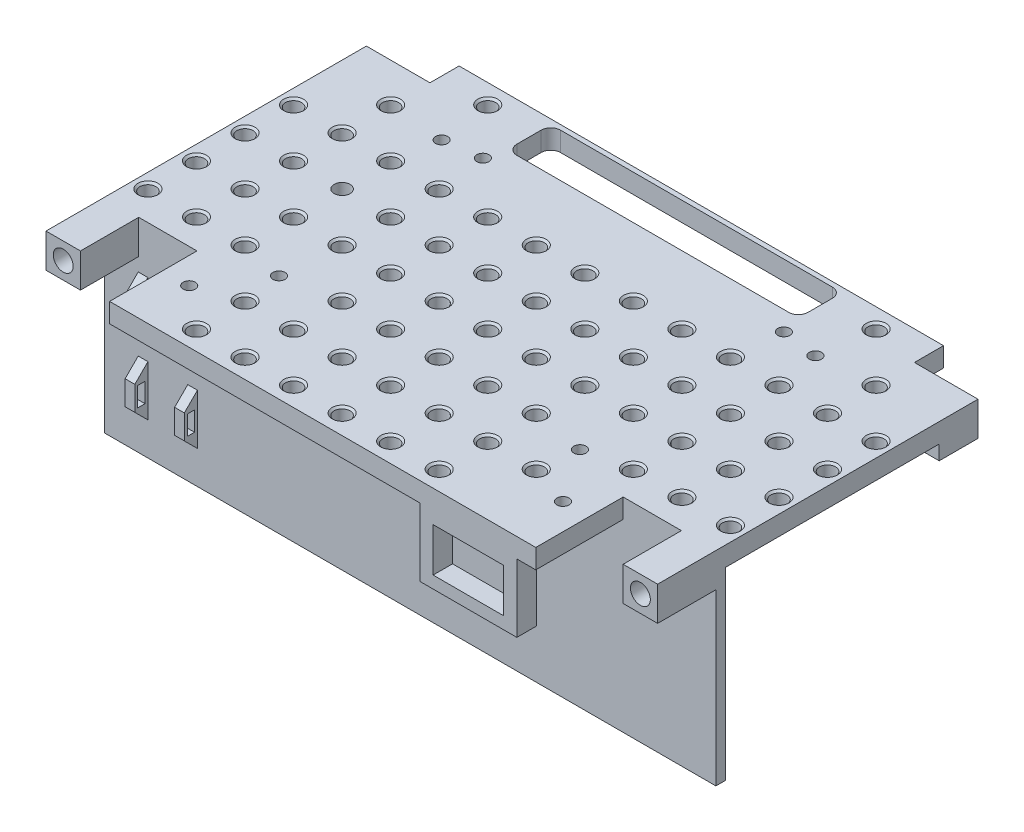
SolidWorks part; units mm, degrees
ref_plane "Front Plane" through (0, 0, 0) normal (0, 0, 1) x (1, 0, 0)
ref_plane "Top Plane" through (0, 0, 0) normal (0, 1, 0) x (1, 0, 0)
ref_plane "Right Plane" through (0, 0, 0) normal (1, 0, 0) x (0, 0, -1)
sketch "Sketch1" plane through (0, 0, 0) normal (0, 1, 0) x (1, 0, 0)
  line L0 (-63, 0) -> (63, 0) construction
  line L1 (-63, -33) -> (-55.9, -33)
  line L2 (-63, -33) -> (-63, 33)
  line L3 (-63, 33) -> (-55.9, 33)
  line L4 (63, -33) -> (63, 33)
  line L5 (-63, -33) -> (63, 33) construction
  line L6 (-63, 33) -> (63, -33) construction
  line L8 (-55.9, 33) -> (-55.9, 40)
  line L9 (-55.9, 40) -> (55.9, 40)
  line L10 (55.9, 33) -> (55.9, 40)
  line L11 (55.9, 33) -> (63, 33)
  line L12 (55.9, -33) -> (55.9, -40)
  line L13 (-55.9, -40) -> (55.9, -40)
  line L14 (-55.9, -33) -> (-55.9, -40)
  line L15 (55.9, -33) -> (63, -33)
  point P0 (0, 0)
  point P10 (0, 40)
  dimension "D1" = 126
  dimension "D2" = 66
  dimension "D3" = 7.1
  dimension "D4" = 7
extrude "Boss-Extrude1" add sketch "Sketch1" along normal blind 4
sketch "Sketch3" plane through (0, 0, 0) normal (0, -1, 0) x (1, 0, 0)
  line L0 (-63, -33) -> (-63, 33) construction
  line L1 (-55.9, -33) -> (-63, -33)
  line L2 (-55.9, -33) -> (-55.9, -25)
  line L3 (-55.9, -25) -> (-63, -25)
  line L4 (-63, -33) -> (-63, -25)
  dimension "D1" = 8
extrude "Boss-Extrude3" add sketch "Sketch3" along normal blind 3
sketch "Sketch4" plane through (0, 0, -33) normal (0, 0, -1) x (-1, 0, 0)
  line L0 (63, -3) -> (55.9, 4) construction
  circle A0 centre (59.45, 0.5) radius 2.05
  dimension "D1" = 4.1
extrude "Cut-Extrude1" cut sketch "Sketch4" against normal blind 7
mirror "Mirror1" about plane through (0, 0, 0) normal (1, 0, 0) of "Cut-Extrude1", "Boss-Extrude3"
mirror "Mirror2" about plane through (0, 0, 0) normal (0, 0, 1) of "Cut-Extrude1", "Boss-Extrude3", "Mirror1"
sketch "Sketch5" plane through (0, 4, 0) normal (0, 1, 0) x (1, 0, 0)
  line L0 (55.9, 40) -> (-55.9, 40) construction
  line L1 (-30, 38) -> (30, 38)
  line L2 (-30, 38) -> (-30, 29)
  line L3 (-30, 29) -> (30, 29)
  line L4 (30, 38) -> (30, 29)
  point P4 (0, 29)
  dimension "D1" = 2
  dimension "D2" = 9
  dimension "D3" = 60
extrude "Cut-Extrude2" cut sketch "Sketch5" against normal through all
sketch "Sketch6" plane through (0, 4, 0) normal (0, 1, 0) x (1, 0, 0)
  line L1 (-38.5, -28) -> (38.5, -28) construction
  line L2 (-38.5, -28) -> (-38.5, 24) construction
  line L3 (-38.5, 24) -> (38.5, 24) construction
  line L4 (38.5, -28) -> (38.5, 24) construction
  line L5 (-38.5, -28) -> (38.5, 24) construction
  line L6 (-38.5, 24) -> (38.5, -28) construction
  circle A0 centre (-38.5, 24) radius 1.25
  circle A1 centre (38.5, 24) radius 1.25
  circle A2 centre (38.5, -28) radius 1.25
  circle A3 centre (-38.5, -28) radius 1.25
  point P0 (0, -2)
  point P9 (0, -2)
  dimension "D4" = 2.5
  dimension "D1" = 77
  dimension "D2" = 52
  dimension "D3" = 2
fillet "Fillet1" radius 2 4 edges at (-30, 2, -38) (-30, 2, -29) (30, 2, -38) (30, 2, -29)
sketch "Sketch7" plane through (0, 4, 0) normal (0, 1, 0) x (1, 0, 0)
  line L0 (55.9, 33) -> (55.9, 40) construction
  line L1 (-55.9, 40) -> (55.9, 40)
  line L2 (-55.9, 40) -> (-55.9, 39)
  line L3 (-55.9, 39) -> (55.9, 39)
  line L4 (55.9, 40) -> (55.9, 39)
  line L5 (-55.9, -33) -> (-55.9, -40) construction
  line L6 (55.9, -40) -> (-55.9, -40)
  line L7 (55.9, -40) -> (55.9, -39)
  line L8 (55.9, -39) -> (-55.9, -39)
  line L9 (-55.9, -40) -> (-55.9, -39)
  dimension "D1" = 1
  dimension "D2" = 1
extrude "Cut-Extrude3" cut sketch "Sketch7" against normal through all
sketch "Sketch8" plane through (0, 0, 0) normal (0, -1, 0) x (1, 0, 0)
  line L0 (63, 25) -> (63, -25) construction
  line L1 (63, 21) -> (-63, 21)
  line L2 (63, 21) -> (63, 19)
  line L3 (63, 19) -> (-63, 19)
  line L4 (-63, 21) -> (-63, 19)
  line L5 (-63, -25) -> (-63, 25) construction
  line L7 (55.9, 39) -> (-55.9, 39) construction
  dimension "D1" = 20
  dimension "D2" = 2
extrude "Boss-Extrude4" add sketch "Sketch8" along normal blind 38
sketch "Sketch9" plane through (0, 4, 0) normal (0, 1, 0) x (1, 0, 0)
  line L0 (63, -21) -> (-63, -21) construction
  line L1 (-55.9, -39) -> (-43.9, -39)
  line L2 (-55.9, -39) -> (-55.9, -21)
  line L3 (-55.9, -21) -> (-43.9, -21)
  line L4 (-43.9, -39) -> (-43.9, -21)
  dimension "D1" = 12
extrude "Cut-Extrude4" cut sketch "Sketch9" against normal blind 10
sketch "Sketch10" plane through (0, -3, 0) normal (0, -1, 0) x (1, 0, 0)
  line L1 (-63, 25) -> (-55.9, 25)
  line L2 (-63, 25) -> (-63, 21)
  line L3 (-63, 21) -> (-55.9, 21)
  line L4 (-55.9, 25) -> (-55.9, 21)
  line L5 (55.9, 25) -> (63, 25)
  line L6 (55.9, 25) -> (55.9, 21)
  line L7 (55.9, 21) -> (63, 21)
  line L8 (63, 25) -> (63, 21)
extrude "Boss-Extrude5" add sketch "Sketch10" against normal up to surface (3 mm away) up to face at (29.4143, 0, 29)
ref_plane "Plane2" through (-56, 0, 0) normal (-1, 0, 0) x (0, 0, 1)
sketch "Sketch12" plane through (-56, 0, 0) normal (-1, 0, 0) x (0, 0, 1)
  line L0 (21, -5.8) -> (21, -16.2)
  line L1 (21, -38) -> (21, -3) construction
  line L2 (21, -16.2) -> (23.7, -13.5)
  line L3 (23.7, -13.5) -> (23.7, -8.5)
  line L4 (23.7, -8.5) -> (21, -5.8)
  line L5 (23.7, -11) -> (21, -11) construction
  line L6 (21, -3) -> (33, -3) construction
  line L7 (23.1, -9) -> (21.6, -9)
  line L8 (23.1, -9) -> (23.1, -13)
  line L9 (23.1, -13) -> (21.6, -13)
  line L10 (21.6, -9) -> (21.6, -13)
  line L11 (21, -20.8) -> (21, -31.2)
  line L12 (21, -31.2) -> (23.7, -28.5)
  line L13 (23.7, -28.5) -> (23.7, -23.5)
  line L14 (23.7, -23.5) -> (21, -20.8)
  line L15 (23.1, -24) -> (21.6, -24)
  line L16 (23.1, -24) -> (23.1, -28)
  line L17 (23.1, -28) -> (21.6, -28)
  line L18 (21.6, -24) -> (21.6, -28)
  line L19 (23.7, -26) -> (21, -26) construction
  point P13 (22.35, -11)
  point P14 (23.1, -11)
  dimension "D1" = 1.5
  dimension "D2" = 0.6
  dimension "D3" = 0.6
  dimension "D4" = 4
  dimension "D5" = 45
  dimension "D6" = 5
  dimension "D7" = 8
  dimension "D8" = 2
extrude "Boss-Extrude6" add sketch "Sketch12" against normal blind 2
ref_plane "Plane3" through (-49.9, 0, 0) normal (1, 0, 0) x (0, 0, -1)
mirror "Mirror3" about plane through (-49.9, 0, 0) normal (1, 0, 0) of "Boss-Extrude6"
sketch "Sketch13" plane through (0, 0, 0) normal (0, -1, 0) x (1, 0, 0)
  line L0 (-28, -29) -> (28, -29) construction
  line L1 (-20, -20.5) -> (20, -20.5)
  line L2 (-20, -20.5) -> (-20, -22.5)
  line L3 (-20, -22.5) -> (20, -22.5)
  line L4 (20, -20.5) -> (20, -22.5)
  point P4 (0, -22.5)
  dimension "D1" = 40
  dimension "D2" = 2
  dimension "D3" = 6.5
extrude "Boss-Extrude7" add sketch "Sketch13" along normal up to surface (38 mm away) up to face at (0, -38, 20)
sketch "Sketch14" plane through (0, 0, 0) normal (1, 0, 0) x (0, 0, -1)
  line L0 (-19, -19) -> (20.5, -19) construction
  line L1 (-19, -38) -> (-19, 0) construction
  line L2 (20.5, -38) -> (20.5, 0) construction
  line L3 (0.75, -38) -> (0.75, 0) construction
  line L4 (-19, 0) -> (25, 0) construction
  line L5 (-21, -31.2) -> (-23.7, -28.5) construction
  line L6 (-23.1, -24) -> (-21.6, -24) construction
  line L7 (-23.1, -28) -> (-23.1, -24) construction
  line L8 (-21.6, -28) -> (-23.1, -28) construction
  line L9 (-21.6, -24) -> (-21.6, -28) construction
  line L10 (-21, -20.8) -> (-21, -31.2) construction
  line L11 (-23.7, -23.5) -> (-21, -20.8) construction
  line L12 (-23.7, -28.5) -> (-23.7, -23.5) construction
  line L13 (-23.1, -13) -> (-23.1, -9) construction
  line L14 (-23.1, -9) -> (-21.6, -9) construction
  line L15 (-21.6, -9) -> (-21.6, -13) construction
  line L16 (-21.6, -13) -> (-23.1, -13) construction
  line L17 (-21, -5.8) -> (-21, -16.2) construction
  line L18 (-21, -16.2) -> (-23.7, -13.5) construction
  line L19 (-23.7, -13.5) -> (-23.7, -8.5) construction
  line L20 (-23.7, -8.5) -> (-21, -5.8) construction
  line L21 (-21, -31.2) -> (-23.7, -28.5) construction
  line L22 (-23.1, -24) -> (-21.6, -24) construction
  line L23 (-23.1, -28) -> (-23.1, -24) construction
  line L24 (-21.6, -28) -> (-23.1, -28) construction
  line L25 (-21.6, -24) -> (-21.6, -28) construction
  line L26 (-21, -20.8) -> (-21, -31.2) construction
  line L27 (-23.7, -23.5) -> (-21, -20.8) construction
  line L28 (-23.7, -28.5) -> (-23.7, -23.5) construction
  line L29 (-23.1, -13) -> (-23.1, -9) construction
  line L30 (-23.1, -9) -> (-21.6, -9) construction
  line L31 (-21.6, -9) -> (-21.6, -13) construction
  line L32 (-21.6, -13) -> (-23.1, -13) construction
  line L33 (-21, -5.8) -> (-21, -16.2) construction
  line L34 (-21, -16.2) -> (-23.7, -13.5) construction
  line L35 (-23.7, -13.5) -> (-23.7, -8.5) construction
  line L36 (-23.7, -8.5) -> (-21, -5.8) construction
  line L37 (25.2, -8.5) -> (22.5, -5.8)
  line L38 (25.2, -13.5) -> (25.2, -8.5)
  line L39 (22.5, -16.2) -> (25.2, -13.5)
  line L40 (22.5, -5.8) -> (22.5, -16.2)
  line L41 (23.1, -13) -> (24.6, -13)
  line L42 (23.1, -9) -> (23.1, -13)
  line L43 (24.6, -9) -> (23.1, -9)
  line L44 (24.6, -13) -> (24.6, -9)
  line L45 (25.2, -28.5) -> (25.2, -23.5)
  line L46 (25.2, -23.5) -> (22.5, -20.8)
  line L47 (22.5, -20.8) -> (22.5, -31.2)
  line L48 (23.1, -24) -> (23.1, -28)
  line L49 (23.1, -28) -> (24.6, -28)
  line L50 (24.6, -28) -> (24.6, -24)
  line L51 (24.6, -24) -> (23.1, -24)
  line L52 (22.5, -31.2) -> (25.2, -28.5)
  point P11 (0.75, -19)
extrude "Boss-Extrude8" add sketch "Sketch14" along normal mid plane 2
sketch "Sketch15" plane through (0, 0, 0) normal (1, 0, 0) x (0, 0, -1)
  line L0 (20.5, 0) -> (20.5, -5)
  line L1 (20.5, -38) -> (20.5, 0) construction
  line L2 (20.5, -5) -> (17.6132, 0)
  line L3 (-19, 0) -> (25, 0) construction
  line L4 (17.6132, 0) -> (20.5, 0)
  dimension "D1" = 60
  dimension "D2" = 5
extrude "Boss-Extrude9" add sketch "Sketch15" against normal up to surface and the other way up to surface up to face at (-20, -19, -21.5) other way up to face at (20, -19, -21.5)
sketch "Sketch16" plane through (0, 0, 39) normal (0, 0, 1) x (1, 0, 0)
  line L0 (40, 0) -> (20, -14) construction
  line L1 (40, 0) -> (20, 0)
  line L2 (40, 0) -> (40, -14)
  line L3 (40, -14) -> (20, -14)
  line L4 (20, 0) -> (20, -14)
  line L5 (55.9, 0) -> (-43.9, 0) construction
  line L6 (22.75, -2.5) -> (37.25, -2.5)
  line L7 (22.75, -2.5) -> (22.75, -11.5)
  line L8 (22.75, -11.5) -> (37.25, -11.5)
  line L9 (37.25, -2.5) -> (37.25, -11.5)
  line L10 (22.75, -2.5) -> (37.25, -11.5) construction
  line L11 (22.75, -11.5) -> (37.25, -2.5) construction
  line L12 (63, -38) -> (63, -3) construction
  point P5 (30, -7)
  dimension "D1" = 20
  dimension "D2" = 14
  dimension "D3" = 14.5
  dimension "D4" = 9
  dimension "D5" = 23
extrude "Boss-Extrude10" add sketch "Sketch16" against normal blind 4
sketch "Sketch17" plane through (0, 0, 0) normal (0, -1, 0) x (1, 0, 0)
  line L6 (-43.9, 21) -> (-55.9, 21) construction
  line L7 (55.9, 39) -> (43.9, 39)
  line L8 (55.9, 39) -> (55.9, 21)
  line L9 (55.9, 21) -> (43.9, 21)
  line L10 (43.9, 39) -> (43.9, 21)
  line L13 (-43.9, 39) -> (-43.9, 21) construction
extrude "Cut-Extrude5" cut sketch "Sketch17" against normal through all
sketch "Sketch18" plane through (0, 4, 0) normal (0, 1, 0) x (1, 0, 0)
  line L5 (-55.9, 39) -> (55.9, 39) construction
  line L6 (55.9, 33) -> (49.9, 33)
  line L7 (55.9, 33) -> (55.9, 39)
  line L8 (55.9, 39) -> (49.9, 39)
  line L9 (49.9, 33) -> (49.9, 39)
  line L11 (-55.9, 33) -> (-49.9, 33)
  line L12 (-55.9, 33) -> (-55.9, 39)
  line L13 (-55.9, 39) -> (-49.9, 39)
  line L14 (-49.9, 33) -> (-49.9, 39)
extrude "Cut-Extrude6" cut sketch "Sketch18" against normal through all
sketch "Sketch20" plane through (0, 4, 0) normal (0, 1, 0) x (1, 0, 0)
  line L0 (-31, 25) -> (31, -17) construction
  line L1 (-31, 25) -> (31, 25) construction
  line L2 (-31, 25) -> (-31, -17) construction
  line L3 (-31, -17) -> (31, -17) construction
  line L4 (31, 25) -> (31, -17) construction
  line L5 (-38.5, 26) -> (38.5, 26) construction
  line L6 (-38.5, 26) -> (-38.5, -26) construction
  line L7 (-38.5, -26) -> (38.5, -26) construction
  line L8 (38.5, 26) -> (38.5, -26) construction
  line L11 (38.5, 26) -> (-38.5, -26) construction
  circle A0 centre (-31, 25) radius 3 construction
  circle A1 centre (-31, -17) radius 3 construction
  circle A2 centre (31, -17) radius 3 construction
  circle A3 centre (31, 25) radius 3 construction
  circle A4 centre (-38.5, 26) radius 3 construction
  circle A5 centre (38.5, 26) radius 3 construction
  circle A6 centre (38.5, -26) radius 3 construction
  circle A7 centre (-38.5, -26) radius 3 construction
  point P18 (0, 4)
  dimension "D3" = 6
  dimension "D1" = 42
  dimension "D2" = 62
  dimension "D4" = 4
  dimension "D6" = 77
  dimension "D7" = 52
sketch "Sketch22" plane through (0, 4, 0) normal (0, 1, 0) x (1, 0, 0)
  circle A0 centre (-31, 25) radius 1.25
  circle A1 centre (31, 25) radius 1.25
  circle A2 centre (31, -17) radius 1.25
  circle A3 centre (-31, -17) radius 1.25
  dimension "D1" = 2.5
extrude "Cut-Extrude7" cut sketch "Sketch22" against normal up to surface (4 mm away) up to face at (15, 0, 33.5)
sketch "Sketch23" plane through (0, 4, 0) normal (0, 1, 0) x (1, 0, 0)
  line L0 (-63, 0) -> (63, 0) construction
  line L1 (63, -33) -> (63, 33) construction
  line L2 (0, -39) -> (0, 39) construction
  line L3 (-49.9, 39) -> (49.9, 39) construction
  line L4 (-63, -5) -> (63, -5) construction
  line L5 (-63, -15) -> (63, -15) construction
  line L9 (-10, -5) -> (-10, -15) construction
  line L10 (-20, -5) -> (-20, -15) construction
  line L11 (-30, -5) -> (-30, -15) construction
  line L12 (-40, -5) -> (-40, -15) construction
  line L13 (-50, -5) -> (-50, -15) construction
  line L14 (-60, -5) -> (-60, -15) construction
  circle A0 centre (0, -5) radius 1.65
  circle A1 centre (0, -15) radius 1.65
  circle A2 centre (-10, -5) radius 1.65
  circle A3 centre (-20, -5) radius 1.65
  circle A4 centre (-30, -5) radius 1.65
  circle A5 centre (-40, -5) radius 1.65
  circle A6 centre (-50, -5) radius 1.65
  circle A7 centre (-60, -5) radius 1.65
  circle A8 centre (-60, -15) radius 1.65
  circle A9 centre (-50, -15) radius 1.65
  circle A10 centre (-40, -15) radius 1.65
  circle A11 centre (-20, -15) radius 1.65
  circle A12 centre (-10, -15) radius 1.65
  point P6 (0, 0)
  point P11 (0, 0)
  point P18 (0, -5)
  point P21 (0, -15)
  dimension "D1" = 3.3
  dimension "D4" = 10
  dimension "D2" = 5
  dimension "D3" = 10
  dimension "D5" = 10
  dimension "D6" = 10
  dimension "D7" = 10
  dimension "D8" = 10
  dimension "D9" = 10
extrude "Cut-Extrude8" cut sketch "Sketch23" against normal through all
mirror "Mirror4" about plane through (0, 0, 0) normal (0, 0, 1) of "Cut-Extrude8"
mirror "Mirror5" about plane through (0, 0, 0) normal (1, 0, 0) of "Mirror4", "Cut-Extrude8"
sketch "Sketch24" plane through (0, 4, 0) normal (0, 1, 0) x (1, 0, 0)
  line L0 (-40, 15) -> (-20, 15) construction
  line L1 (20, 15) -> (40, 15) construction
  line L2 (-40, 15) -> (-40, 39) construction
  line L3 (-49.9, 39) -> (49.9, 39) construction
  line L4 (-50, 15) -> (-50, 33) construction
  line L5 (-49.9, 33) -> (-63, 33) construction
  line L6 (-50, 25) -> (-40, 25) construction
  line L7 (-50, 35) -> (-40, 35) construction
  line L8 (40, 15) -> (40, 39) construction
  line L9 (50, 15) -> (50, 33) construction
  line L10 (63, 33) -> (49.9, 33) construction
  line L11 (40, 25) -> (50, 25) construction
  line L12 (50, 35) -> (40, 35) construction
  line L13 (-30, -5) -> (-30, -39) construction
  line L14 (43.9, -39) -> (-43.9, -39) construction
  line L16 (30, -5) -> (30, -39) construction
  line L17 (-20, -5) -> (-20, -39) construction
  line L18 (-10, -5) -> (-10, -39) construction
  line L19 (0, -5) -> (0, -39) construction
  line L20 (10, -5) -> (10, -39) construction
  line L21 (20, -5) -> (20, -39) construction
  line L22 (-30, -25) -> (30, -25) construction
  line L23 (-30, -35) -> (30, -35) construction
  circle A0 centre (-30, 15) radius 1.65
  circle A1 centre (30, 15) radius 1.65
  circle A2 centre (-40, 15) radius 1.65 construction
  circle A3 centre (-40, 35) radius 1.65
  circle A4 centre (-40, 25) radius 1.65 construction
  circle A5 centre (-50, 25) radius 1.65
  circle A6 centre (40, 25) radius 1.65 construction
  circle A7 centre (50, 25) radius 1.65
  circle A8 centre (40, 35) radius 1.65
  circle A9 centre (-10, 15) radius 1.65 construction
  circle A10 centre (-20, -15) radius 1.65 construction
  circle A11 centre (30, -25) radius 1.65
  circle A13 centre (-30, -25) radius 1.65
  circle A14 centre (-30, -35) radius 1.65
  circle A15 centre (-10, -25) radius 1.65
  circle A16 centre (-10, -35) radius 1.65
  circle A17 centre (0, -25) radius 1.65
  circle A18 centre (0, -35) radius 1.65
  circle A19 centre (10, -25) radius 1.65
  circle A20 centre (10, -35) radius 1.65
  circle A21 centre (20, -35) radius 1.65
  circle A22 centre (20, -25) radius 1.65
  circle A23 centre (-20, -25) radius 1.65
  circle A24 centre (-20, -35) radius 1.65
  circle A26 centre (20, -15) radius 1.65 construction
  dimension "D1" = 10
  dimension "D2" = 10
  dimension "D3" = 10
  dimension "D4" = 10
  dimension "D5" = 10
  dimension "D6" = 10
extrude "Cut-Extrude9" cut sketch "Sketch24" against normal through all
chamfer "Chamfer1" distance 0.4 angle 45 131 edges at (-60, 0, 6.65) (-60, 4, 6.65) (-60, 0, -13.35) (-60, 4, -16.65) (-60, 0, -3.35) (-60, 4, -6.65) (-50, 0, -23.35) (-50, 4, -23.35) (-50, 0, -13.35) (-50, 4, -16.65) (-50, 0, -3.35) (-50, 4, -6.65) (-50, 0, 6.65) (-50, 4, 6.65) (-60, 0, 16.65) (-60, 4, 16.65) (-50, 0, 16.65) (-50, 4, 16.65) (-40, 0, 16.65) (-40, 4, 16.65) (-40, 0, 6.65) (-40, 4, 6.65) (-40, 0, -33.35) (-40, 4, -33.35) (-40, 0, -13.35) (-40, 4, -16.65) (-30, 0, -13.35) (-30, 4, -13.35) (-30, 0, -3.35) (-30, 4, -6.65) (-20, 0, 6.65) (-20, 4, 6.65) (-10, 0, 16.65) (-10, 4, 16.65) (60, 0, 16.65) (60, 4, 16.65) (60, 0, 6.65) (60, 4, 6.65) (60, 0, -3.35) (60, 4, -6.65) (60, 0, -13.35) (60, 4, -16.65) (50, 0, -23.35) (50, 4, -23.35) (40, 0, -13.35) (40, 4, -16.65) (40, 0, -33.35) (40, 4, -33.35) (50, 0, -13.35) (50, 4, -16.65) (50, 0, -3.35) (50, 4, -6.65) (50, 0, 16.65) (50, 4, 16.65) (50, 0, 6.65) (50, 4, 6.65) (40, 0, 6.65) (40, 4, 6.65) (40, 0, 16.65) (40, 4, 16.65) (40, 0, -3.35) (40, 4, -6.65) (30, 0, -3.35) (30, 4, -6.65) (30, 0, -13.35) (30, 4, -13.35) (20, 0, -13.35) (20, 4, -16.65) (20, 0, -3.35) (20, 4, -6.65) (30, 0, 6.65) (30, 4, 6.65) (20, 0, 6.65) (20, 4, 6.65) (20, 0, 16.65) (20, 4, 16.65) (30, 0, 26.65) (30, 4, 26.65) (20, 0, 26.65) (20, 4, 26.65) (10, 0, 36.65) (10, 4, 36.65) (10, 0, 26.65) (10, 4, 26.65) (10, 0, 16.65) (10, 4, 16.65) (10, 0, 6.65) (10, 4, 6.65) (10, 0, -3.35) (10, 4, -6.65) (10, 0, -13.35) (10, 4, -16.65) (0, 0, -13.35) (0, 4, -16.65) (0, 0, -3.35) (0, 4, -6.65) (0, 0, 6.65) (0, 4, 6.65) (0, 0, 16.65) (0, 4, 16.65) (0, 0, 26.65) (0, 4, 26.65) (0, 0, 36.65) (0, 4, 36.65) (-10, 0, 36.65) (-10, 4, 36.65) (-10, 0, 26.65) (-10, 4, 26.65) (-10, 0, 6.65) (-10, 4, 6.65) (-10, 0, -3.35) (-10, 4, -6.65) (-10, 0, -13.35) (-10, 4, -16.65) (-20, 0, -13.35) (-20, 4, -16.65) (-20, 0, -3.35) (-20, 4, -6.65) (-20, 0, 16.65) (-20, 4, 16.65) (-20, 0, 26.65) (-20, 4, 26.65) (-20, 0, 36.65) (-20, 4, 36.65) (-30, 0, 36.65) (-30, 4, 36.65) (-30, 0, 26.65) (-30, 4, 26.65) (-30, 0, 6.65) (-30, 4, 6.65) (20, 4, 36.65)
extrude "Cut-Extrude10" cut sketch "Sketch6" against normal up to surface (4 mm away) up to face at (30, 0, 27.05)
